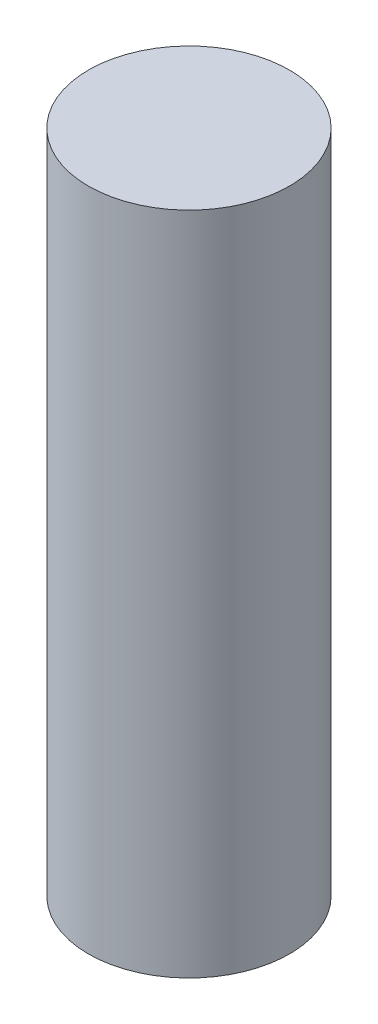
SolidWorks part; units mm, degrees
ref_plane "Front Plane" through (0, 0, 0) normal (0, 0, 1) x (1, 0, 0)
ref_plane "Top Plane" through (0, 0, 0) normal (0, 1, 0) x (1, 0, 0)
ref_plane "Right Plane" through (0, 0, 0) normal (1, 0, 0) x (0, 0, -1)
sketch "Sketch1" plane through (0, 0, 0) normal (0, 1, 0) x (1, 0, 0)
  line L0 (-1.7103, 2.675) -> (1.7103, 2.675)
  line L1 (0, 2.675) -> (0, -3.175) construction
  arc A0 (-1.7103, 2.675) -> (1.7103, 2.675) centre (0, 0) ccw
  dimension "D1" = 6.35
  dimension "D2" = 5.85
extrude "Boss-Extrude1" add sketch "Sketch1" along normal blind 15
sketch "Sketch2" plane through (0, 15, 0) normal (0, 1, 0) x (1, 0, 0)
  circle A0 centre (0, 0) radius 3.175
  arc A1 (-1.7103, 2.675) -> (1.7103, 2.675) centre (0, 0) ccw construction
extrude "Boss-Extrude2" add sketch "Sketch2" along normal blind 6
